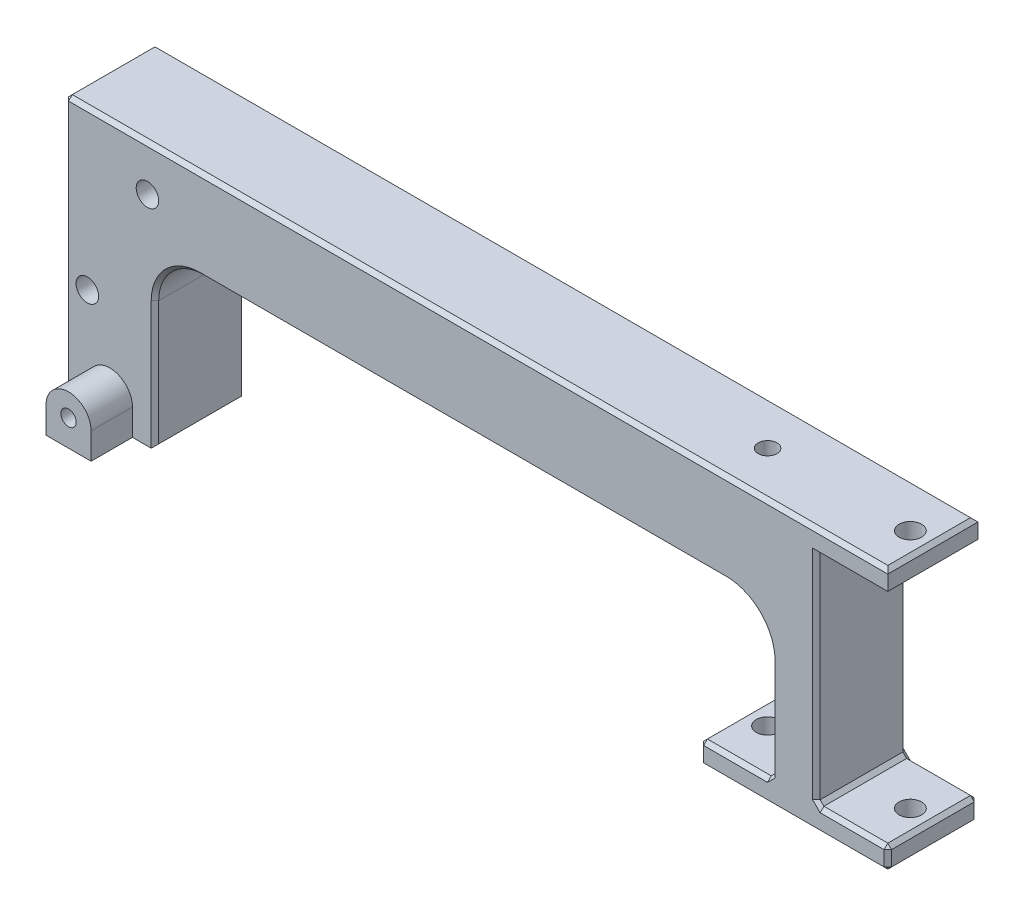
SolidWorks part; units mm, degrees
material "AISI 1020"
ref_plane "Front Plane" through (0, 0, 0) normal (0, 0, 1) x (1, 0, 0)
ref_plane "Top Plane" through (0, 0, 0) normal (0, 1, 0) x (1, 0, 0)
ref_plane "Right Plane" through (0, 0, 0) normal (1, 0, 0) x (0, 0, -1)
sketch "Sketch1" plane through (0, 0, 0) normal (0, 0, 1) x (1, 0, 0)
  line L0 (0, 0) -> (0, 35)
  line L1 (0, 35) -> (109.5, 35)
  line L2 (109.5, 35) -> (109.5, 32)
  line L3 (109.5, 32) -> (100, 32)
  line L4 (100, 32) -> (100, 3)
  line L5 (100, 3) -> (109.5, 3)
  line L6 (109.5, 3) -> (109.5, 0)
  line L7 (109.5, 0) -> (84.5, 0)
  line L8 (84.5, 0) -> (84.5, 3)
  line L9 (84.5, 3) -> (94, 3)
  line L10 (94, 3) -> (94, 17)
  line L11 (88, 23) -> (18, 23)
  line L12 (12, 17) -> (12, 0)
  line L13 (12, 0) -> (0, 0)
  arc A0 (94, 17) -> (88, 23) centre (88, 17) ccw
  arc A1 (18, 23) -> (12, 17) centre (18, 17) ccw
  circle A2 centre (11, 29) radius 1.5
  circle A3 centre (3, 14) radius 1.5
  point P17 (109.5, 1.5)
  dimension "D6" = 6
  dimension "D11" = 3
  dimension "D1" = 35
  dimension "D2" = 3
  dimension "D3" = 3
  dimension "D4" = 9.5
  dimension "D5" = 9.5
  dimension "D7" = 70
  dimension "D8" = 12
  dimension "D9" = 25
  dimension "D10" = 12
  dimension "D12" = 11
  dimension "D13" = 6
  dimension "D14" = 15
  dimension "D15" = 3
extrude "Boss-Extrude1" add sketch "Sketch1" along normal mid plane 12
sketch "Sketch2" plane through (0, 0, 6) normal (0, 0, 1) x (1, 0, 0)
  line L0 (0, 0) -> (12, 0) construction
  line L1 (0, 35) -> (0, 0) construction
  line L2 (3, 3.5) -> (3, 0)
  line L3 (9, 3.5) -> (9, 0)
  line L4 (9, 0) -> (3, 0)
  arc A0 (9, 3.5) -> (3, 3.5) centre (6, 3.5) ccw
  dimension "D1" = 3
  dimension "D2" = 3.5
  dimension "D3" = 6
extrude "Boss-Extrude2" add sketch "Sketch2" along normal blind 5.5
sketch "Sketch5" plane through (0, 0, 11.5) normal (0, 0, 1) x (1, 0, 0)
  point P0 (6, 3.5)
hole_wizard "M2.5x0.45 Tapped Hole1" positions "Sketch5" profile "Sketch4" tap size "M2.5x0.45" standard "ANSI Metric"
sketch "Sketch4" plane through (6, 3.5, 11.5) normal (1, 0, 0) x (0, -1, 0)
  line L0 (0, 0) -> (0, 6.85)
  line L1 (0, 6.85) -> (1.025, 6.2341)
  line L2 (1.025, 6.2341) -> (1.025, 0)
  line L5 (1.025, 0) -> (0, 0)
  line L10 (0, 6.85) -> (-1.025, 6.2341) construction
  line L11 (0, -6.35) -> (0, 107.95) construction
  dimension "Tap Drill Dia." = 2.05
  dimension "Tap Drill Depth" = 6.85
  dimension "Drill Angle" = 118
cosmetic thread "Hole Thread1" parameters "D1"=5.5, "D2"=2.5
sketch "Sketch6" plane through (0, 3, 0) normal (0, 1, 0) x (1, 0, 0)
  line L0 (109.5, -6) -> (100, -6) construction
  line L1 (109.5, -6) -> (109.5, 6) construction
  line L2 (94, 6) -> (84.5, 6) construction
  circle A0 centre (87.5, 0) radius 1.5
  circle A1 centre (106.5, 0) radius 1.5
  dimension "D1" = 3
  dimension "D4" = 19
  dimension "D2" = 6
  dimension "D3" = 3
  dimension "D5" = 6
extrude "Cut-Extrude1" cut sketch "Sketch6" against normal up to next
sketch "Sketch7" plane through (0, 35, 0) normal (0, 1, 0) x (1, 0, 0)
  circle A0 centre (106.5, 0) radius 1.5 construction
  circle A1 centre (106.5, 0) radius 1.5
extrude "Cut-Extrude2" cut sketch "Sketch7" against normal up to next
sketch "Sketch10" plane through (0, 35, 0) normal (0, 1, 0) x (1, 0, 0)
  line L0 (109.5, -6) -> (0, -6) construction
  circle A0 centre (106.5, 0) radius 1.5 construction
  point P0 (87.5, 0)
  dimension "D1" = 19
  dimension "D2" = 6
hole_wizard "M3x0.5 Tapped Hole1" positions "Sketch10" profile "Sketch9" tap size "M3x0.5" standard "ANSI Metric"
cosmetic thread "Hole Thread2" parameters "D1"=13, "D2"=3
sketch "Sketch9" plane through (87.5, 35, 0) normal (1, 0, 0) x (0, 0, 1)
  line L0 (0, 0) -> (0, 15.2511)
  line L1 (0, 15.2511) -> (1.25, 14.5)
  line L2 (1.25, 14.5) -> (1.25, 0)
  line L5 (1.25, 0) -> (0, 0)
  line L10 (0, 15.2511) -> (-1.25, 14.5) construction
  line L11 (0, -6.35) -> (0, 107.95) construction
  dimension "Tap Drill Dia." = 2.5
  dimension "Tap Drill Depth" = 14.5
  dimension "Drill Angle" = 118
chamfer "Chamfer1" distance 0.5 angle 45 40 edges at (12, 8.5, -6) (12, 8.5, 6) (13.7574, 21.2426, -6) (13.7574, 21.2426, 6) (53, 23, -6) (53, 23, 6) (92.2426, 21.2426, -6) (92.2426, 21.2426, 6) (97, 0, 6) (109.5, 0, 0) (84.5, 0, 0) (94, 3, 0) (94, 10, -6) (89.25, 3, -6) (84.5, 1.5, 6) (94, 10, 6) (89.25, 3, 6) (84.5, 3, 0) (84.5, 1.5, -6) (97, 0, -6) (100, 3, 0) (109.5, 1.5, 6) (109.5, 1.5, -6) (104.75, 32, -6) (109.5, 32, 0) (104.75, 32, 6) (100, 17.5, -6) (104.75, 3, -6) (109.5, 3, 0) (104.75, 3, 6) (100, 17.5, 6) (0, 17.5, -6) (12, 0, 0) (6, 0, -6) (0, 35, 0) (0, 0, 0) (54.75, 35, -6) (109.5, 35, 0) (54.75, 35, 6) (0, 17.5, 6)
